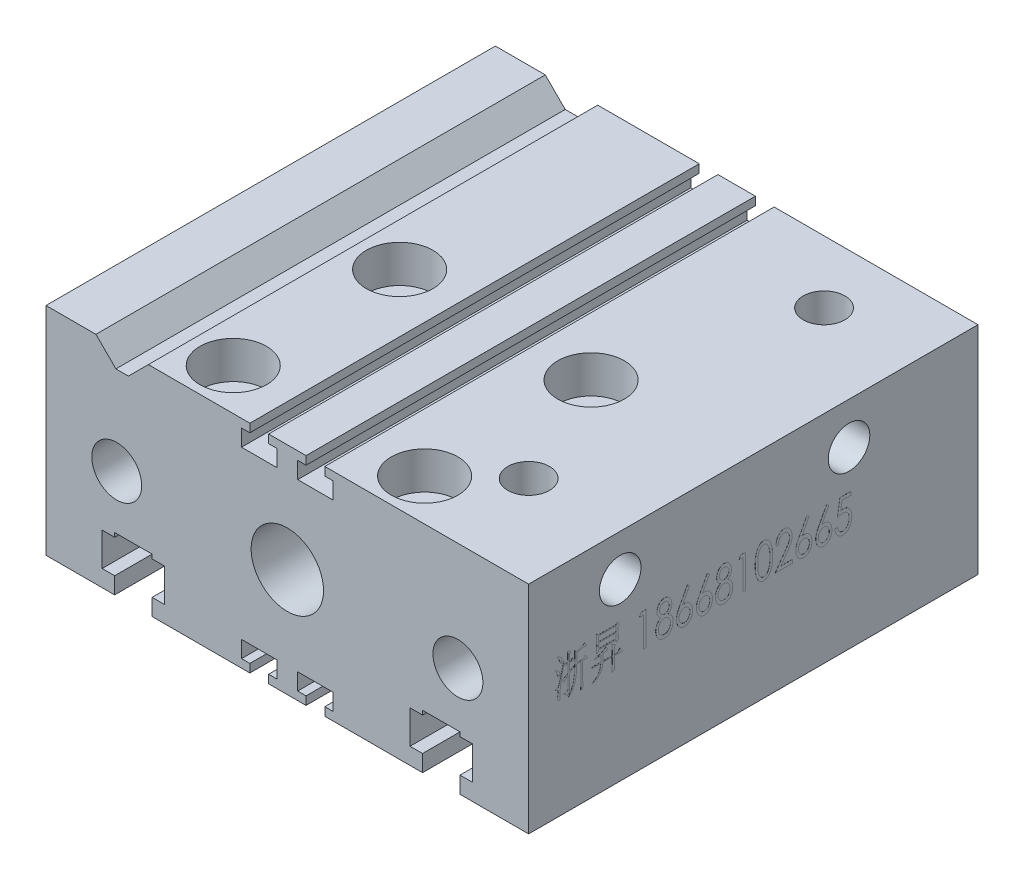
SolidWorks part; units mm, degrees
ref_plane "前视基准面" through (0, 0, 0) normal (0, 0, 1) x (1, 0, 0)
ref_plane "上视基准面" through (0, 0, 0) normal (0, 1, 0) x (1, 0, 0)
ref_plane "右视基准面" through (0, 0, 0) normal (1, 0, 0) x (0, 0, -1)
sketch "草图1" plane through (0, 0, 0) normal (0, 1, 0) x (1, 0, 0)
  line L0 (0, 0) -> (0, 54) construction
  line L1 (-29, 54) -> (29, 54)
  line L2 (-29, 54) -> (-29, 0)
  line L3 (-29, 0) -> (29, 0)
  line L4 (29, 54) -> (29, 0)
  line L5 (-11.5, 0) -> (-11.5, 54) construction
  line L6 (18, 54) -> (18, 0) construction
  line L7 (4.35, 0) -> (4.35, -5)
  line L8 (-29, -5) -> (29, -5)
  line L9 (-29, -5) -> (-29, -13)
  line L10 (-29, -13) -> (29, -13)
  line L11 (29, -5) -> (29, -13)
  line L12 (29, 0) -> (71, 0)
  circle A0 centre (18, 46.5) radius 2.5
  point P4 (29, 25)
  point P8 (0, 25)
  point P11 (-11.5, 5)
  point P12 (-11.5, 25)
  point P15 (18, 46.5)
  point P16 (18, 11)
  point P19 (29, 11)
  point P20 (29, 13.5)
  point P21 (29, 38.5)
  point P28 (0, 51)
  point P29 (0, 48)
  point P30 (-11.5, 15)
  point P31 (18, 54)
  point P33 (-11.5, 44)
  dimension "D2" = 38.5
  dimension "P" = 5
  dimension "D1" = 54
  dimension "B" = 58
  dimension "AC" = 29
  dimension "行程" = 25
  dimension "KB" = 23
  dimension "MB" = 5
  dimension "MC" = 20
  dimension "PB" = 18
  dimension "PD" = 11
  dimension "PF" = 7.5
  dimension "PC" = 11
  dimension "PE" = 13.5
  dimension "D3" = 8.7
  dimension "AD" = 8
  dimension "AB" = 13
  dimension "D4" = 67
  dimension "JA" = 3
  dimension "KA" = 6
  dimension "KC" = 15
  dimension "A" = 42
  dimension "LA" = 10
sketch "草图2" plane through (0, 0, 0) normal (0, 0, 1) x (1, 0, 0)
  line L0 (-29, 0) -> (0, 0) construction
  line L1 (-29, 13) -> (29, 13)
  line L2 (-29, 13) -> (-29, -13)
  line L3 (-29, -13) -> (-20.75, -13)
  line L4 (29, 13) -> (29, -13)
  line L5 (-29, 0) -> (29, 0) construction
  line L6 (0, 0) -> (0, 13) construction
  line L7 (-11.5, 13) -> (-11.5, -13) construction
  line L8 (-7.5, 13) -> (-7.5, 8.5)
  line L9 (-7.5, 8.5) -> (-9.25, 8.5)
  line L10 (-9.25, 8.5) -> (-9.25, -13)
  line L11 (29, 8) -> (24, 8)
  line L12 (-29, 0) -> (29, 0) construction
  line L13 (-11.75, 0) -> (-11.25, 0) construction
  line L14 (-11.75, 1.5) -> (-11.25, 1.5)
  line L15 (-11.75, -1.5) -> (-11.25, -1.5)
  line L16 (-9.25, -3) -> (-9, -3)
  line L17 (-2.25, -13) -> (-2.25, -12)
  line L18 (-9, -3) -> (-9, -13)
  line L19 (-4.5, -12) -> (-4.5, -13)
  line L20 (-16.25, -13) -> (-16.25, -11)
  line L21 (-16.25, -11) -> (-14.75, -11)
  line L22 (-14.75, -11) -> (-14.75, -7)
  line L23 (-14.75, -7) -> (-16.25, -7)
  line L24 (-22.25, -7) -> (-22.25, -11)
  line L25 (-22.25, -11) -> (-20.75, -11)
  line L26 (-20.75, -11) -> (-20.75, -13)
  line L27 (-23, 13) -> (-20.6, 10.6)
  line L28 (-20.6, 10.6) -> (-19.1, 10.6)
  line L29 (-19.1, 10.6) -> (-16.7, 13)
  line L36 (-20.75, -7) -> (-22.25, -7)
  line L37 (-20.75, -6.5) -> (-16.25, -6.5)
  line L38 (-20.75, -6.5) -> (-20.75, -7)
  line L39 (-16.25, -13) -> (29, -13)
  line L40 (-16.25, -6.5) -> (-16.25, -7)
  line L41 (-20.75, -13) -> (-16.25, -13) construction
  line L42 (-2.25, -12) -> (-1.25, -12)
  line L43 (-5.5, -10) -> (-1.25, -10)
  line L44 (-5.5, -10) -> (-5.5, -12)
  line L45 (-5.5, -12) -> (-4.5, -12)
  line L46 (-1.25, -10) -> (-1.25, -12)
  circle A0 centre (-20.5, 0) radius 3
  circle A1 centre (20.5, 0) radius 3
  circle A2 centre (-25, 9) radius 2
  circle A3 centre (-25, -9) radius 2
  circle A4 centre (11.5, 0) radius 1.5
  arc A5 (-11.75, 1.5) -> (-11.75, -1.5) centre (-11.75, 0) ccw
  arc A6 (-11.25, -1.5) -> (-11.25, 1.5) centre (-11.25, 0) ccw
  point P48 (-11.5, 0)
  point P52 (-18.5, -13)
  point P64 (-9.75, 0)
  point P65 (-13.25, 0)
  dimension "D1" = 1
  dimension "D" = 6
  dimension "D7" = 10.4
  dimension "L" = 4
  dimension "D10" = 2.4
  dimension "K" = 3
  dimension "C" = 26
  dimension "G" = 41
  dimension "U" = 7.5
  dimension "W" = 4
  dimension "V" = 4.5
  dimension "X" = 2
  dimension "Y" = 6.5
  dimension "S" = 37
  dimension "D2" = 1
  dimension "D3" = 2
  dimension "M" = 8
  dimension "MA" = 4.5
  dimension "N" = 4.5
  dimension "D4" = 2.25
  dimension "D5" = 2
  dimension "D6" = 135
  dimension "LC" = 18
  dimension "LB" = 50
  dimension "D8" = 2
  dimension "D9" = 5
  dimension "PA" = 8
  dimension "J" = 3.5
  dimension "R" = 5
  dimension "RA" = 10
sketch "草图3" plane through (0, 0, 0) normal (0, 0, 1) x (1, 0, 0)
  line L0 (0, 11) -> (0, 0) construction
  line L1 (-28, 11) -> (28, 11)
  line L2 (-28, 11) -> (-28, -11)
  line L3 (-28, -11) -> (28, -11)
  line L4 (28, 11) -> (28, -11)
  line L5 (-29, 0) -> (29, 0) construction
  line L6 (0, 0) -> (0, -11) construction
  line L7 (-29, 0) -> (29, 0) construction
  circle A0 centre (-24, 7) radius 2
  circle A1 centre (-25, 9) radius 2 construction
  dimension "BA" = 56
  dimension "CA" = 22
  dimension "LD" = 48
  dimension "LE" = 14
sketch "草图4" plane through (0, 0, 0) normal (0, 0, 1) x (1, 0, 0)
  line L0 (-14.75, -7) -> (-16.25, -7) construction
  line L1 (-14.75, -11) -> (-14.75, -7) construction
  line L2 (-16.25, -11) -> (-14.75, -11) construction
  line L3 (-16.25, -13) -> (-16.25, -11) construction
  line L4 (-16.25, -13) -> (29, -13) construction
  line L6 (-29, 13) -> (29, 13) construction
  line L7 (-29, 13) -> (-29, -13) construction
  line L8 (-29, -13) -> (-20.75, -13) construction
  line L9 (-20.75, -11) -> (-20.75, -13) construction
  line L10 (-22.25, -11) -> (-20.75, -11) construction
  line L11 (-22.25, -7) -> (-22.25, -11) construction
  line L12 (-20.75, -7) -> (-22.25, -7) construction
  line L13 (-20.75, -6.5) -> (-20.75, -7) construction
  line L14 (-20.75, -6.5) -> (-16.25, -6.5) construction
  line L15 (-16.25, -6.5) -> (-16.25, -7) construction
  line L26 (-23, 13) -> (-20.6, 10.6) construction
  line L27 (-20.6, 10.6) -> (-19.1, 10.6) construction
  line L28 (-19.1, 10.6) -> (-16.7, 13) construction
  line L29 (-14.75, -7) -> (-16.25, -7)
  line L30 (-14.75, -11) -> (-14.75, -7)
  line L31 (-16.25, -11) -> (-14.75, -11)
  line L32 (-16.25, -13) -> (-16.25, -11)
  line L33 (-16.25, -13) -> (0, -13)
  line L35 (-29, 13) -> (-23, 13)
  line L36 (-29, 13) -> (-29, -13)
  line L37 (-29, -13) -> (-20.75, -13)
  line L38 (-20.75, -11) -> (-20.75, -13)
  line L39 (-22.25, -11) -> (-20.75, -11)
  line L40 (-22.25, -7) -> (-22.25, -11)
  line L41 (-20.75, -7) -> (-22.25, -7)
  line L42 (-20.75, -6.5) -> (-20.75, -7)
  line L43 (-20.75, -6.5) -> (-16.25, -6.5)
  line L44 (-16.25, -6.5) -> (-16.25, -7)
  line L45 (0, 13) -> (0, -13)
  line L52 (-16.7, 13) -> (0, 13)
  line L55 (-23, 13) -> (-20.6, 10.6)
  line L56 (-20.6, 10.6) -> (-19.1, 10.6)
  line L57 (-19.1, 10.6) -> (-16.7, 13)
  circle A4 centre (-20.5, 0) radius 3 construction
  circle A5 centre (-20.5, 0) radius 3
extrude "凸台-拉伸1" add sketch "草图4" against normal up to vertex (54 mm away) up to point (0, 0, -54)
sketch "草图5" plane through (0, 0, 0) normal (0, 0, 1) x (1, 0, 0)
  line L0 (-5.5, -12) -> (-4.5, -12) construction
  line L1 (-4.5, -12) -> (-4.5, -13) construction
  line L2 (-5.5, -10) -> (-5.5, -12) construction
  line L3 (-5.5, -10) -> (-1.25, -10) construction
  line L4 (-1.25, -10) -> (-1.25, -12) construction
  line L5 (-2.25, -12) -> (-1.25, -12) construction
  line L6 (-2.25, -13) -> (-2.25, -12) construction
  line L7 (-5.5, -12) -> (-4.5, -12)
  line L8 (-4.5, -12) -> (-4.5, -13)
  line L9 (-5.5, -10) -> (-5.5, -12)
  line L10 (-5.5, -10) -> (-1.25, -10)
  line L11 (-1.25, -10) -> (-1.25, -12)
  line L12 (-2.25, -12) -> (-1.25, -12)
  line L13 (-2.25, -13) -> (-2.25, -12)
  line L14 (-4.5, -13) -> (-2.25, -13)
extrude "切除-拉伸1" cut sketch "草图5" against normal through all
mirror "镜向1" about plane through (0, 0, 0) normal (0, 1, 0) of "切除-拉伸1"
sketch "草图6" plane through (0, 13, 0) normal (0, 1, 0) x (-1, 0, 0)
  circle A0 centre (11.5, -25) radius 4
  circle A1 centre (11.5, -5) radius 4
  point P6 (7.5, -5)
extrude "切除-拉伸2" cut sketch "草图6" against normal up to vertex (4.5 mm away) up to point (-7.5, 8.5, 0)
sketch "草图7" plane through (0, 8.5, 0) normal (0, 1, 0) x (1, 0, 0)
  circle A0 centre (-11.5, 25) radius 2.25
  circle A1 centre (-11.5, 5) radius 2.25
  point P6 (-9.25, 25)
extrude "切除-拉伸3" cut sketch "草图7" against normal up to vertex (21.5 mm away) up to point (-9.25, -13, 0)
mirror "镜向2" about plane through (0, 0, 0) normal (1, 0, 0) of bodies 105
sketch "草图8" plane through (0, 0, 0) normal (0, 0, 1) x (1, 0, 0)
  line L0 (16.7, 13) -> (23, 13)
  line L1 (23, 13) -> (20.6, 10.6)
  line L2 (20.6, 10.6) -> (19.1, 10.6)
  line L3 (19.1, 10.6) -> (16.7, 13)
extrude "凸台-拉伸2" add sketch "草图8" against normal up to surface (54 mm away) up to face at (-17.5, 0, -54)
sketch "草图9" plane through (0, 13, 0) normal (0, 1, 0) x (1, 0, 0)
  circle A0 centre (18, 46.5) radius 2.5
  circle A1 centre (18, 11) radius 2.5
  circle A2 centre (18, 46.5) radius 2.5 construction
extrude "切除-拉伸4" cut sketch "草图9" against normal blind 5
sketch "草图10" plane through (29, 0, 0) normal (1, 0, 0) x (0, 0, -1)
  circle A0 centre (11, 8) radius 2.5
  circle A1 centre (38.5, 8) radius 2.5
  dimension "D1" = 5
extrude "切除-拉伸5" cut sketch "草图10" against normal up to vertex (5 mm away) up to point (24, 8, 0)
sketch "草图11" plane through (0, 0, 0) normal (0, 0, 1) x (1, 0, 0)
  line L0 (-29, 0) -> (29, 0) construction
  circle A0 centre (0, 0) radius 4.35
extrude "切除-拉伸6" cut sketch "草图11" against normal up to vertex (46.5 mm away) up to point (18, 0, -46.5)
sketch "草图12" plane through (0, 0, -54) normal (0, 0, -1) x (-1, 0, 0)
  line L0 (11.75, 1.5) -> (11.25, 1.5) construction
  line L1 (11.75, -1.5) -> (11.25, -1.5) construction
  line L2 (11.75, 1.5) -> (11.25, 1.5)
  line L3 (11.75, -1.5) -> (11.25, -1.5)
  circle A0 centre (-11.5, 0) radius 1.5 construction
  arc A1 (11.75, -1.5) -> (11.75, 1.5) centre (11.75, 0) ccw construction
  arc A2 (11.25, 1.5) -> (11.25, -1.5) centre (11.25, 0) ccw construction
  circle A3 centre (-11.5, 0) radius 1.5
  arc A4 (11.75, -1.5) -> (11.75, 1.5) centre (11.75, 0) ccw
  arc A5 (11.25, 1.5) -> (11.25, -1.5) centre (11.25, 0) ccw
extrude "切除-拉伸7" cut sketch "草图12" against normal up to vertex (3 mm away) up to point (0, 0, -51)
sketch "草图13" plane through (0, 0, -51) normal (0, 0, -1) x (-1, 0, 0)
  line L0 (11.5, 13) -> (11.5, -13) construction
  circle A0 centre (11.5, 0) radius 1.5
  circle A2 centre (-11.5, 0) radius 1.5
  circle A3 centre (-11.5, 0) radius 1.5
  dimension "D1" = 0
extrude "凸台-拉伸4" add sketch "草图13" against normal up to vertex (3 mm away) up to point (0, 0, -48)
sketch "草图14" plane through (0, -13, 0) normal (0, -1, 0) x (1, 0, 0)
  circle A0 centre (-11.5, -15) radius 1.5
  circle A1 centre (11.5, -15) radius 1.5
  dimension "D1" = 3
extrude "切除-拉伸8" cut sketch "草图14" against normal blind 6
sketch "草图15" plane through (0, -13, 0) normal (0, -1, 0) x (1, 0, 0)
  line L0 (-11.75, -15) -> (-11.25, -15) construction
  line L1 (-11.75, -13.5) -> (-11.25, -13.5)
  line L2 (-11.75, -16.5) -> (-11.25, -16.5)
  arc A0 (-11.75, -13.5) -> (-11.75, -16.5) centre (-11.75, -15) ccw
  arc A1 (-11.25, -16.5) -> (-11.25, -13.5) centre (-11.25, -15) ccw
  point P2 (-11.5, -15)
  point P7 (-9.75, -15)
  point P8 (-13.25, -15)
  dimension "D1" = 3.5
  dimension "D2" = 1.5
extrude "切除-拉伸9" cut sketch "草图15" against normal blind 3
sketch "草图16" plane through (0, 0, 0) normal (0, 0, 1) x (1, 0, 0)
  line L0 (-28, 11) -> (28, 11) construction
  line L1 (28, 11) -> (28, -11) construction
  line L2 (-28, -11) -> (28, -11) construction
  line L3 (-28, 11) -> (-28, -11) construction
  line L4 (-28, 11) -> (28, 11)
  line L5 (28, 11) -> (28, -11)
  line L6 (-28, -11) -> (28, -11)
  line L7 (-28, 11) -> (-28, -11)
extrude "凸台-拉伸5" add sketch "草图16" along normal up to vertex (13 mm away) from vertex at 5 separate body starting at point (29, 0, 5)
sketch "草图18" plane through (0, 0, 13) normal (0, 0, 1) x (1, 0, 0)
  circle A0 centre (20.5, 0) radius 3 construction
  circle A1 centre (-20.5, 0) radius 3 construction
  circle A2 centre (20.5, 0) radius 3
  circle A3 centre (-20.5, 0) radius 3
extrude "凸台-拉伸6" add sketch "草图18" against normal up to vertex (67 mm away) up to point (18, 0, -54)
sketch "草图19" plane through (0, 0, 13) normal (0, 0, 1) x (1, 0, 0)
  circle A0 centre (0, 0) radius 4.35
extrude "凸台-拉伸7" add sketch "草图19" against normal up to vertex (59.5 mm away) up to point (18, 0, -46.5)
sketch "草图20" plane through (0, 0, 13) normal (0, 0, 1) x (1, 0, 0)
  circle A0 centre (-24, 7) radius 2 construction
  circle A1 centre (-24, 7) radius 2
extrude "切除-拉伸10" cut sketch "草图20" against normal up to vertex (8 mm away) up to point (-29, 0, 5)
mirror "镜向3" about plane through (0, 0, 0) normal (0, 1, 0) of "切除-拉伸10"
mirror "镜向4" about plane through (0, 0, 0) normal (1, 0, 0) of "镜向3", "切除-拉伸10"
sketch "草图21" plane through (0, 0, 13) normal (0, 0, 1) x (1, 0, 0)
  line L0 (-11.75, 1.5) -> (-11.25, 1.5) construction
  line L1 (-11.75, -1.5) -> (-11.25, -1.5) construction
  line L2 (-11.75, 1.5) -> (-11.25, 1.5)
  line L3 (-11.75, -1.5) -> (-11.25, -1.5)
  circle A0 centre (11.5, 0) radius 1.5 construction
  arc A1 (-11.25, -1.5) -> (-11.25, 1.5) centre (-11.25, 0) ccw construction
  arc A2 (-11.75, 1.5) -> (-11.75, -1.5) centre (-11.75, 0) ccw construction
  circle A3 centre (11.5, 0) radius 1.5
  arc A4 (-11.25, -1.5) -> (-11.25, 1.5) centre (-11.25, 0) ccw
  arc A5 (-11.75, 1.5) -> (-11.75, -1.5) centre (-11.75, 0) ccw
extrude "切除-拉伸11" cut sketch "草图21" against normal blind 3
sketch "草图22" plane through (0, 0, 10) normal (0, 0, 1) x (1, 0, 0)
  circle A0 centre (-11.5, 0) radius 1.5
  circle A1 centre (11.5, 0) radius 1.5
  circle A2 centre (11.5, 0) radius 1.5
  dimension "D1" = 0
extrude "切除-拉伸12" cut sketch "草图22" against normal blind 3
sketch "草图23" plane through (0, 0, 0) normal (0, 1, 0) x (1, 0, 0)
  line L0 (0, 0) -> (0, -25)
  line L1 (-29, 0) -> (29, 0) construction
  line L2 (0, -25) -> (1, -25)
  line L3 (0, 0) -> (29, 0)
  dimension "D1" = 1
  dimension "D2" = 25
delete or keep bodies "实体-删除1" type delete bodies bodies 123
sketch "草图24" plane through (29, -8.2719, -81.7181) normal (1, 0, 0) x (0, 0, -1)
  line L0 (-78.7181, 13.7719) -> (-78.7181, 7.6052) construction
  line L1 (-27.7181, -4.7281) -> (-81.7181, -4.7281) construction
  line L2 (-78.7181, 7.6052) -> (-78.7181, 1.4385) construction
  line L3 (-78.7181, 1.4385) -> (-78.7181, -4.7281) construction
  line L4 (-78.7181, 7.6052) -> (-81.7181, 7.6052) construction
  line L5 (-81.7181, 21.2719) -> (-81.7181, -4.7281) construction
  line L9 (-78.7181, 7.6052) -> (-75.7181, 7.6052) construction
  circle A2 centre (-70.7181, 16.2719) radius 2.5 construction
  circle A3 centre (-70.7181, 16.2719) radius 2.5 construction
  text T0 "浙昇 18668102665" font "Century Gothic" height in points 15
  point P14 (-70.7181, 13.7719)
  dimension "D1" = 3
extrude "LOGO" add sketch "草图24" along normal blind 0.01
